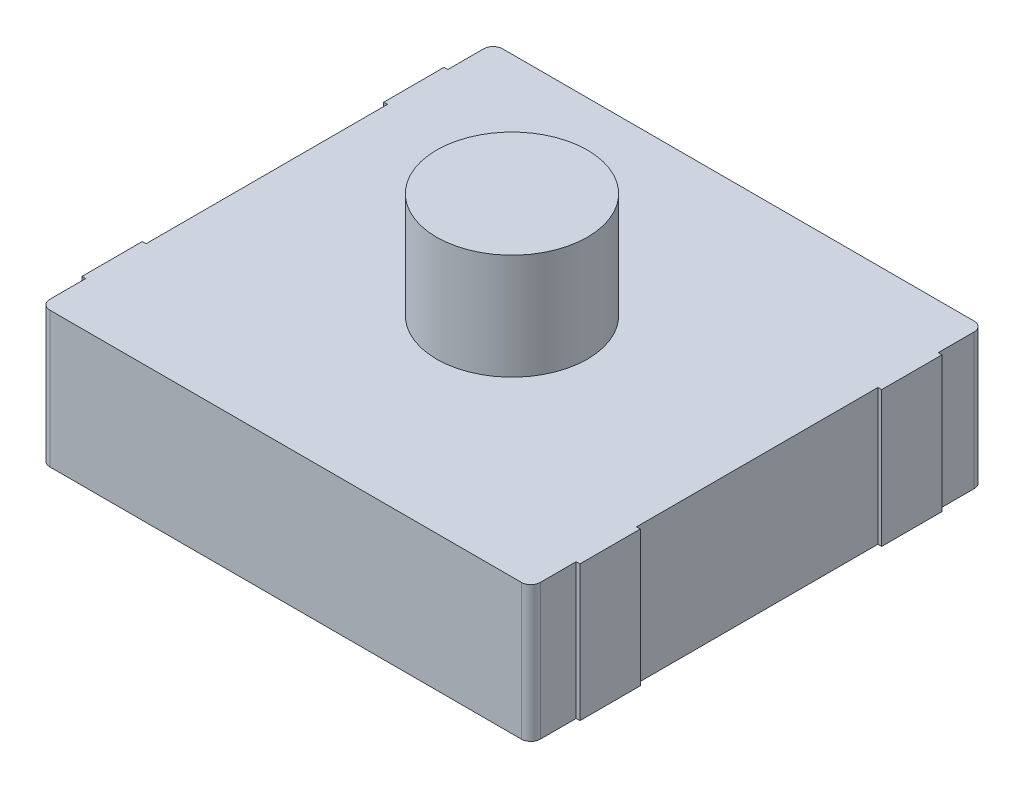
SolidWorks part; units mm, degrees
ref_plane "Front Plane" through (0, 0, 0) normal (0, 0, 1) x (1, 0, 0)
ref_plane "Top Plane" through (0, 0, 0) normal (0, 1, 0) x (1, 0, 0)
ref_plane "Right Plane" through (0, 0, 0) normal (1, 0, 0) x (0, 0, -1)
sketch "Sketch1" plane through (0, 0, 0) normal (0, 1, 0) x (1, 0, 0)
  line L0 (0, 0) -> (0, 39.4469) construction
  line L1 (0, -55) -> (0, 55) construction
  line L2 (0, 0) -> (36.4494, 0) construction
  line L3 (-55, 0) -> (55, 0) construction
  line L5 (-3.25, 3) -> (3.25, 3)
  line L6 (-3.25, 3) -> (-3.25, -3)
  line L7 (-3.25, -3) -> (3.25, -3)
  line L8 (3.25, 3) -> (3.25, -3)
  dimension "D1" = 6.5
  dimension "D2" = 6
extrude "Boss-Extrude1" add sketch "Sketch1" along normal blind 1.8
sketch "Sketch2" plane through (0, 0, 0) normal (0, -1, 0) x (1, 0, 0)
  line L0 (0, 0) -> (0, 3.1406) construction
  line L1 (-3.3, 2.4) -> (-2.3, 2.4)
  line L2 (-3.3, 2.4) -> (-3.3, 1.6)
  line L3 (-3.3, 1.6) -> (-2.3, 1.6)
  line L4 (-2.3, 2.4) -> (-2.3, 1.6)
  line L5 (-3.3, -1.6) -> (-2.3, -1.6)
  line L6 (-3.3, -1.6) -> (-3.3, -2.4)
  line L7 (-3.3, -2.4) -> (-2.3, -2.4)
  line L8 (-2.3, -1.6) -> (-2.3, -2.4)
  line L9 (0, 0) -> (-3.848, 0) construction
  line L10 (-3.3, 2) -> (-2.3, 2) construction
  line L11 (-3.3, -2) -> (-2.3, -2) construction
  line L12 (3.3, -2) -> (2.3, -2) construction
  line L13 (3.3, 2) -> (2.3, 2) construction
  line L14 (2.3, -1.6) -> (2.3, -2.4)
  line L15 (3.3, -2.4) -> (2.3, -2.4)
  line L16 (3.3, -1.6) -> (3.3, -2.4)
  line L17 (3.3, -1.6) -> (2.3, -1.6)
  line L18 (2.3, 2.4) -> (2.3, 1.6)
  line L19 (3.3, 1.6) -> (2.3, 1.6)
  line L20 (3.3, 2.4) -> (3.3, 1.6)
  line L21 (3.3, 2.4) -> (2.3, 2.4)
  dimension "D1" = 0.8
  dimension "D2" = 4
  dimension "D3" = 3.3
  dimension "D4" = 1
extrude "Boss-Extrude2" add sketch "Sketch2" against normal up to surface (1.8 mm away) up to face at (0, 1.8, 0)
sketch "Sketch3" plane through (0, 1.8, 0) normal (0, 1, 0) x (1, 0, 0)
  circle A0 centre (0, 0) radius 1
  dimension "D1" = 2
extrude "Boss-Extrude3" add sketch "Sketch3" along normal blind 1.4
fillet "Fillet1" radius 0.125 4 edges at (3.25, 0.9, -3) (-3.25, 0.9, -3) (-3.25, 0.9, 3) (3.25, 0.9, 3)
